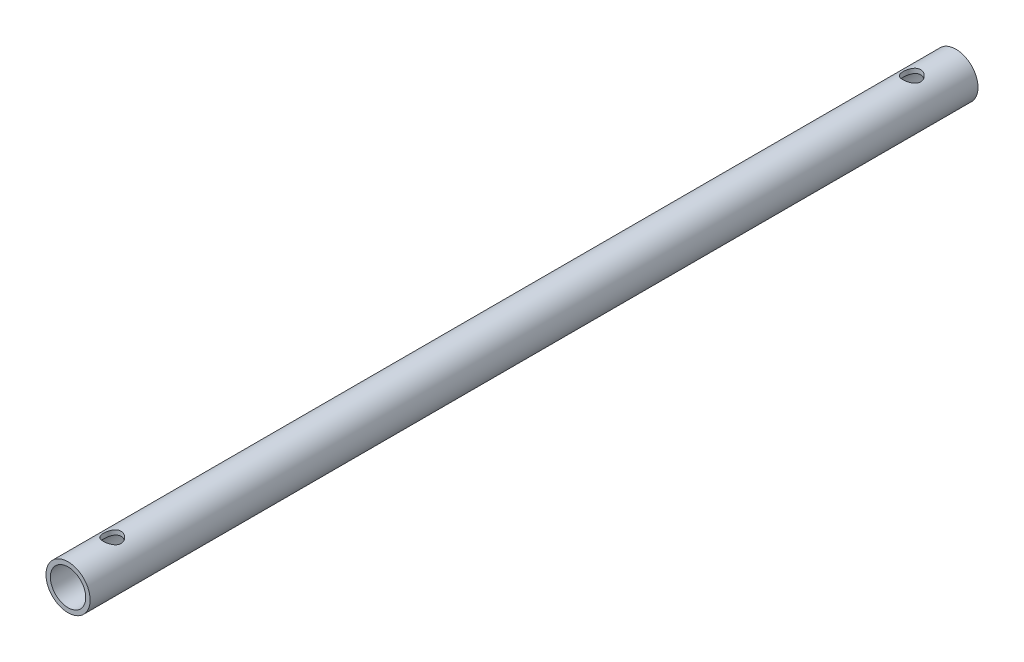
SolidWorks part; units mm, degrees
ref_plane "前视基准面" through (0, 0, 0) normal (0, 0, 1) x (1, 0, 0)
ref_plane "上视基准面" through (0, 0, 0) normal (0, 1, 0) x (1, 0, 0)
ref_plane "右视基准面" through (0, 0, 0) normal (1, 0, 0) x (0, 0, -1)
sketch "草图1" plane through (0, 0, 0) normal (0, 0, 1) x (1, 0, 0)
  circle A0 centre (0, 0) radius 5
  circle A1 centre (0, 0) radius 4
  dimension "D1" = 10
  dimension "D2" = 1
extrude "凸台-拉伸1" add sketch "草图1" along normal mid plane 201
sketch "草图2" plane through (0, 0, 0) normal (0, 1, 0) x (1, 0, 0)
  line L0 (-4, -100.5) -> (4, -100.5) construction
  line L1 (0, -90.5) -> (0, 90.5) construction
  circle A0 centre (0, -90.5) radius 2
  circle A1 centre (0, 90.5) radius 2
  dimension "D1" = 10
  dimension "D2" = 4
  dimension "D3" = 181
extrude "切除-拉伸1" cut sketch "草图2" against normal through all both and the other way through all
